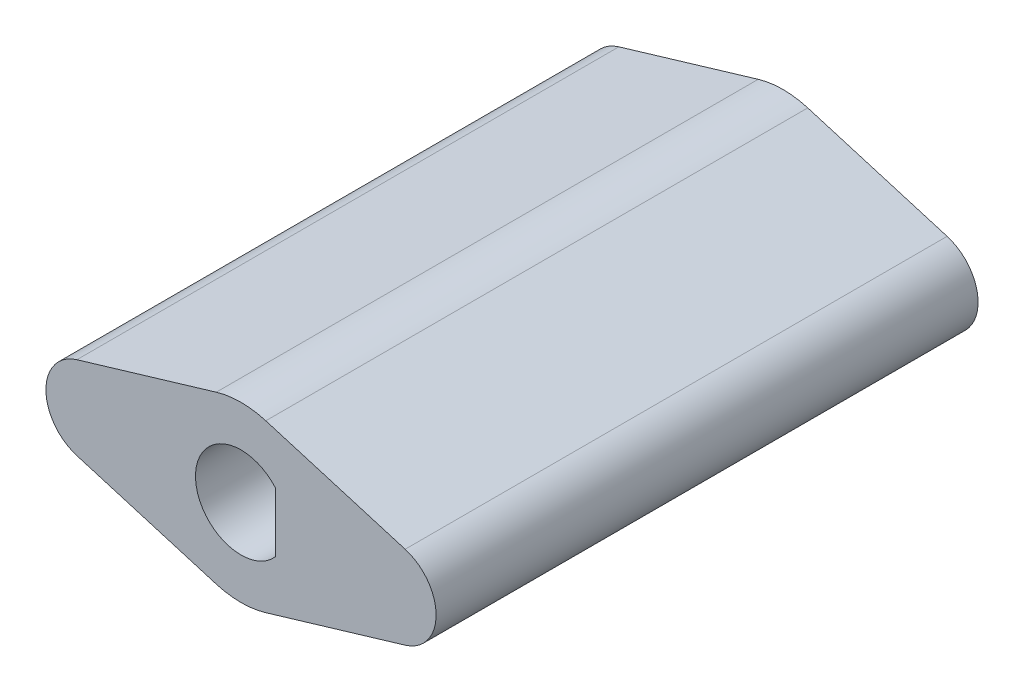
SolidWorks part; units mm, degrees
ref_plane "Front Plane" through (0, 0, 0) normal (0, 0, 1) x (1, 0, 0)
ref_plane "Top Plane" through (0, 0, 0) normal (0, 1, 0) x (1, 0, 0)
ref_plane "Right Plane" through (0, 0, 0) normal (1, 0, 0) x (0, 0, -1)
sketch "Sketch1" plane through (0, 0, 0) normal (0, 0, 1) x (1, 0, 0)
  line L0 (-11.43, 0) -> (0, 0) construction
  line L1 (-9.6157, 2.4341) -> (-1.4514, 4.8682)
  line L2 (-9.6157, -2.4341) -> (-1.4514, -4.8682)
  line L3 (2.032, 1.7274) -> (2.032, -1.7274)
  line L4 (11.43, 0) -> (0, 0) construction
  line L5 (9.6157, 2.4341) -> (1.4514, 4.8682)
  line L6 (9.6157, -2.4341) -> (1.4514, -4.8682)
  arc A0 (-1.4514, -4.8682) -> (1.4514, -4.8682) centre (0, 0) ccw
  arc A1 (2.032, 1.7274) -> (2.032, -1.7274) centre (0, 0) ccw
  arc A2 (-9.6157, 2.4341) -> (-9.6157, -2.4341) centre (-8.89, 0) ccw
  arc A3 (9.6157, -2.4341) -> (9.6157, 2.4341) centre (8.89, 0) ccw
  arc A4 (1.4514, 4.8682) -> (-1.4514, 4.8682) centre (0, 0) ccw
  dimension "D2" = 5.334
  dimension "D3" = 10.16
  dimension "D4" = 5.08
  dimension "D7" = 5.08
  dimension "D1" = 11.43
  dimension "D5" = 2.032
  dimension "D6" = 11.43
extrude "Boss-Extrude1" add sketch "Sketch1" along normal mid plane 31.75
equation "\"D7@Sketch1\"=\"D4@Sketch1\""
equation "\"D6@Sketch1\"=\"D1@Sketch1\""
